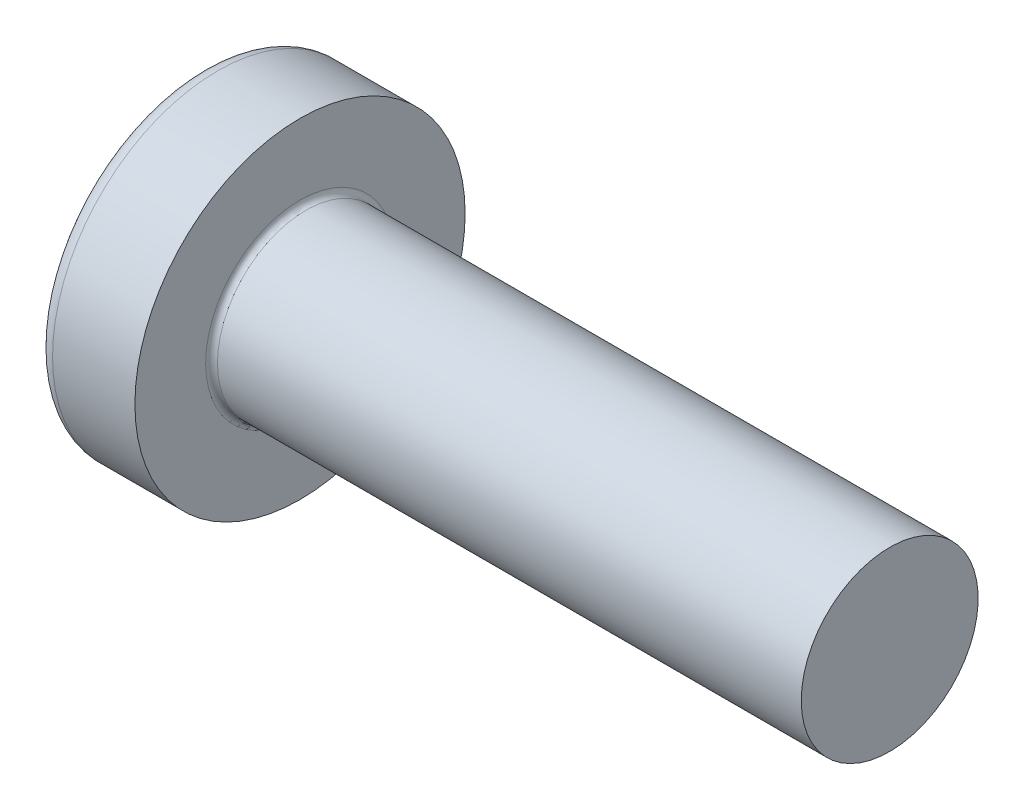
SolidWorks part; units mm, degrees
ref_plane "Plane1" through (0, 0, 0) normal (0, 0, 1) x (1, 0, 0)
ref_plane "Plane2" through (0, 0, 0) normal (0, 1, 0) x (1, 0, 0)
ref_plane "Plane3" through (0, 0, 0) normal (1, 0, 0) x (0, 0, -1)
sketch "BodySke" plane through (0, 0, 0) normal (0, 0, 1) x (1, 0, 0)
  line L0 (2.4, 1.5) -> (2.4, 2.8)
  line L1 (2.65, 6.35) -> (2.65, -3.175) construction
  line L2 (-25.4, 0) -> (127, 0) construction
  line L3 (12.4, 0) -> (0, 0)
  line L4 (2.4, 1.5) -> (12.4, 1.5)
  line L5 (12.4, 1.5) -> (12.4, 0)
  line L6 (1.0035, 2.8) -> (2.4, 2.8)
  line L8 (-2.6, 6.35) -> (-2.6, -3.175) construction
  arc A0 (0.7754, 2.6744) -> (0, 0) centre (5, 0) ccw
  arc A2 (0.7754, 2.6744) -> (1.0035, 2.8) centre (1.0035, 2.53) cw
  dimension "Head_fillet_rad" = 0.27
  dimension "Head_crown_rad" = 5
  dimension "Head_ht" = 2.4
  dimension "Diameter" = 3
  dimension "Length" = 10
  dimension "Head_dia" = 5.6
  dimension "Advance" = 0.5
  dimension "Thread_nom" = 15
revolve "Base-Revolve" add sketch "BodySke"
cosmetic thread "ThreadCosmetic" [suppressed]
fillet "Fillet1" radius 0.1 1 edges at (2.4, 0, 1.5)
sketch "Sketch3" plane through (0, 0, 0) normal (1, 0, 0) x (0, 0, -1)
  line L0 (0.37, -1.4) -> (-0.37, -1.4)
  line L1 (0.37, -1.4) -> (0.37, 1.4)
  line L2 (-0.37, 1.4) -> (0.37, 1.4)
  line L3 (-0.37, 1.4) -> (-0.37, -1.4)
  dimension "D1" = 1.4
  dimension "Cross_dia" = 2.8
  dimension "D2" = 0.37
  dimension "Cross_width" = 0.74
ref_plane "Plane4" through (1.75, 0, 0) normal (1, 0, 0) x (0, 0, -1)
sketch "Sketch4" plane through (1.75, 0, 0) normal (1, 0, 0) x (0, 0, -1)
  line L0 (0.37, -0.5275) -> (-0.37, -0.5275)
  line L1 (0.37, -0.5275) -> (0.37, 0.5275)
  line L2 (-0.37, 0.5275) -> (0.37, 0.5275)
  line L3 (-0.37, 0.5275) -> (-0.37, -0.5275)
  dimension "D1" = 0.74
  dimension "D2" = 1.055
  dimension "D3" = 0.37
  dimension "D4" = 0.5275
loft "Recess" cut profiles "Sketch3", "Sketch4"
pattern_circular "RecPat" count 2 every 90 about axis through (0, 0, 0) along (1, 0, 0) of "Recess"
sketch "RecCorSke" plane through (0, 0, 0) normal (0, 0, 1) x (1, 0, 0)
  line L0 (-3.175, 0) -> (15.875, 0) construction
  line L1 (-25.4, 0) -> (127, 0) construction
  line L2 (0, 0) -> (0, 0.6784)
  line L3 (0, 0.6784) -> (1.75, 0.556)
  line L4 (1.75, 0.556) -> (1.9307, 0)
  line L5 (1.9307, 0) -> (0, 0)
  dimension "Diameter" = 1.112
  dimension "Depth" = 1.75
  dimension "Draft_angle" = 4
  dimension "Bottom_angle" = 18
revolve "RecessCore" cut sketch "RecCorSke" angle 360 about L0
sketch "ThdSchSke" plane through (0, 0, 0) normal (0, 0, 1) x (1, 0, 0)
  line L0 (3.4, -1.2195) -> (3.2036, -1.5)
  line L1 (3.4, -1.2195) -> (3.5964, -1.5)
  line L2 (3.5964, -1.5) -> (3.5964, -1.875)
  line L3 (-3.175, 0) -> (5.1513, 0) construction
  line L5 (3.5964, -1.875) -> (3.2036, -1.875)
  line L6 (3.2036, -1.875) -> (3.2036, -1.5)
  dimension "Thread_minor" = 2.439
  dimension "Diameter" = 3
  dimension "Start" = 3.4
  dimension "SideAngle" = 55
  dimension "VeeAngle" = 70
  dimension "Overcut" = 3.75
revolve "ThreadSchematic" [suppressed] cut sketch "ThdSchSke" angle 360 about L3
pattern_linear "ThdSchPat" [suppressed]
equation "\"D1@Sketch3\" = \"Cross_dia@Sketch3\" / 2"
equation "\"D2@Sketch3\" = \"Cross_width@Sketch3\" / 2"
equation "\"Depth@RecCorSke\" = \"Cross_depth@Plane4\""
equation "\"D1@Sketch4\" = \"Cross_width@Sketch3\""
equation "\"D2@Sketch4\" = \"Cross_dia@Sketch3\" - 2.0 * \"Cross_depth@Plane4\" * tan(26.5  * 0.017453292)"
equation "\"D3@Sketch4\" = \"D1@Sketch4\" / 2"
equation "\"D4@Sketch4\" = \"D2@Sketch4\" / 2"
equation "\"Thread_length@ThreadCosmetic\" = ((sgn( (\"Length@BodySke\" - \"Advance@BodySke\" * 2.0 ) - \"Thread_nom@BodySke\" )-1)*( (\"Length@BodySke\" - \"Advance@BodySke\" * 2.0 ) - \"Thread_nom@BodySke\" ))/-2+ \"Thread_nom@BodySke\""
equation "\"Thread_minor@ThdSchSke\" = \"Thread_minor@ThreadCosmetic\""
equation "\"Diameter@ThdSchSke\" = \"Diameter@BodySke\""
equation "\"Overcut@ThdSchSke\" = \"Diameter@BodySke\" * 1.25"
equation "\"Start@ThdSchSke\" = \"Head_ht@BodySke\" + \"Length@BodySke\" - \"Thread_length@ThreadCosmetic\"  '---Non-countersunk---"
equation "\"Num_threads@ThdSchPat\" = int( \"Thread_length@ThreadCosmetic\" / \"Advance@BodySke\" + 0.999 )  + 1"
equation "\"Advance@ThdSchPat\" = \"Thread_length@ThreadCosmetic\" /  (\"Num_threads@ThdSchPat\" - 1) 'relax it"
